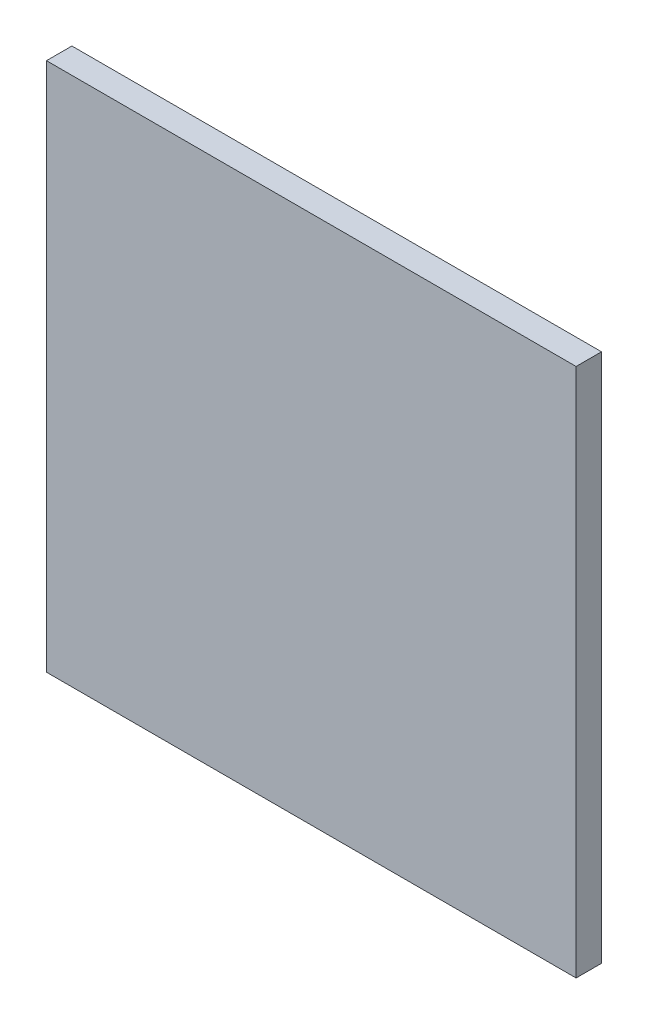
SolidWorks part; units mm, degrees
material "1060 Alloy"
ref_plane "Front Plane" through (0, 0, 0) normal (0, 0, 1) x (1, 0, 0)
ref_plane "Top Plane" through (0, 0, 0) normal (0, 1, 0) x (1, 0, 0)
ref_plane "Right Plane" through (0, 0, 0) normal (1, 0, 0) x (0, 0, -1)
sketch "Sketch1" plane through (0, 0, 0) normal (0, 0, 1) x (1, 0, 0)
  line L1 (0, 0) -> (125, 0)
  line L2 (0, 0) -> (0, 125)
  line L3 (0, 125) -> (125, 125)
  line L4 (125, 0) -> (125, 125)
  dimension "D1" = 125
  dimension "D2" = 125
extrude "Plate" add sketch "Sketch1" along normal blind 6 contours L3 L4 L1 L2
ref_plane "Plane1" through (62.5, 0, 0) normal (-1, 0, 0) x (0, 0, 1)
